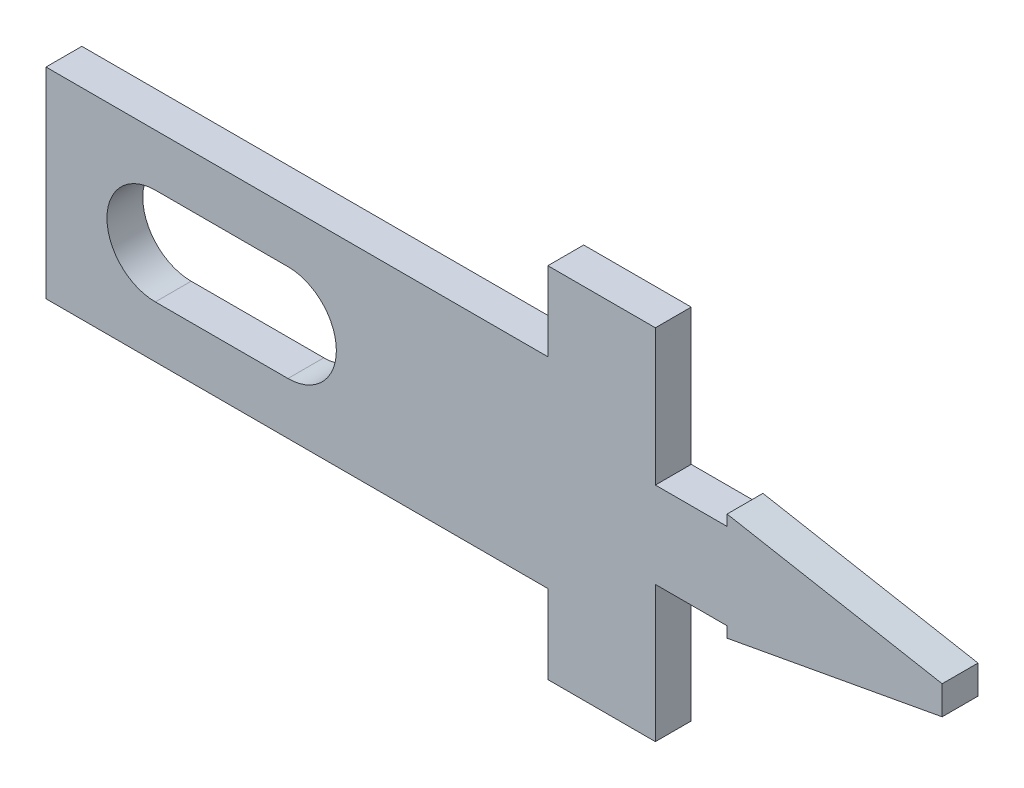
SolidWorks part; units mm, degrees
ref_plane "Front Plane" through (0, 0, 0) normal (0, 0, 1) x (1, 0, 0)
ref_plane "Top Plane" through (0, 0, 0) normal (0, 1, 0) x (1, 0, 0)
ref_plane "Right Plane" through (0, 0, 0) normal (1, 0, 0) x (0, 0, -1)
sketch "Sketch2" plane through (0, 0, 0) normal (0, 0, 1) x (1, 0, 0)
  line L0 (-6.25, 0) -> (6.25, 0) construction
  line L1 (-6.25, -1.4) -> (-6.25, 1.4)
  line L2 (-6.25, 1.4) -> (0.75, 1.4)
  line L3 (0.75, 1.4) -> (0.75, 2.5)
  line L4 (0.75, 2.5) -> (2.25, 2.5)
  line L5 (2.25, 2.5) -> (2.25, 0.6)
  line L6 (2.25, 0.6) -> (3.25, 0.6)
  line L7 (3.25, 0.6) -> (3.25, 0.75)
  line L8 (3.25, 0.75) -> (6.25, 0.2)
  line L9 (6.25, 0.2) -> (6.25, -0.2)
  line L10 (-2.875, 0.675) -> (-4.725, 0.675)
  line L11 (3.25, -0.75) -> (6.25, -0.2)
  line L12 (3.25, -0.6) -> (3.25, -0.75)
  line L13 (2.25, -0.6) -> (3.25, -0.6)
  line L14 (2.25, -2.5) -> (2.25, -0.6)
  line L15 (0.75, -2.5) -> (2.25, -2.5)
  line L16 (0.75, -1.4) -> (0.75, -2.5)
  line L17 (-6.25, -1.4) -> (0.75, -1.4)
  line L18 (-2.875, -0.675) -> (-4.725, -0.675)
  arc A0 (-2.875, -0.675) -> (-2.875, 0.675) centre (-2.875, 0) ccw
  arc A1 (-4.725, 0.675) -> (-4.725, -0.675) centre (-4.725, 0) ccw
  point P3 (-4.8567, 0.6085)
  point P4 (0, 0)
  dimension "D1" = 12.5
  dimension "D2" = 1.4
  dimension "D3" = 1.5
  dimension "D4" = 2.5
  dimension "D5" = 1
  dimension "D6" = 0.2
  dimension "D7" = 0.6
  dimension "D8" = 0.75
  dimension "D9" = 4
  dimension "D12" = 1.35
extrude "Boss-Extrude1" add sketch "Sketch2" along normal blind 0.5
